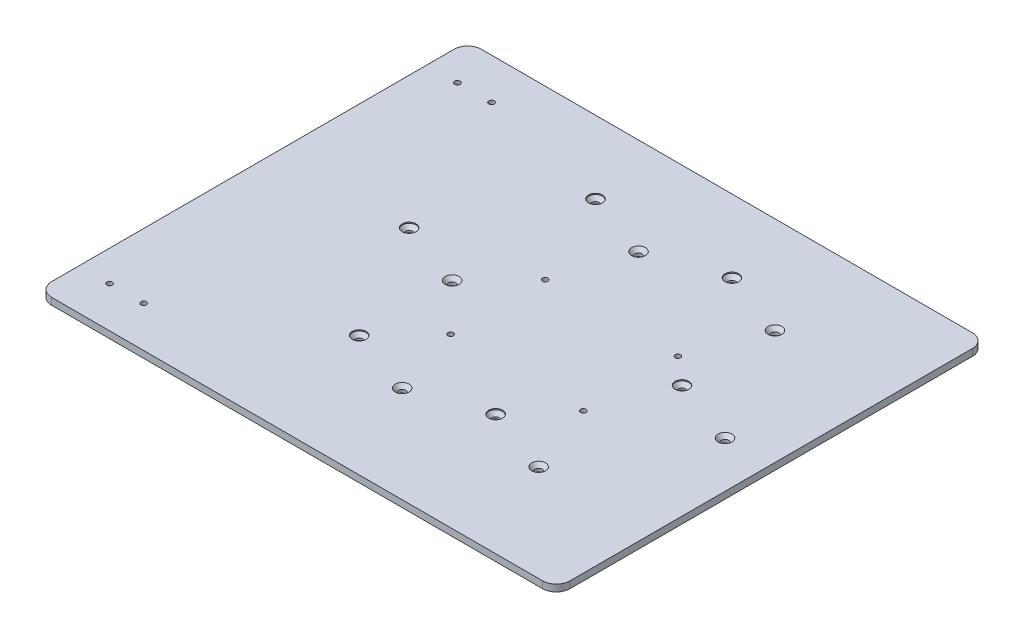
SolidWorks part; units mm, degrees
material "6061 Alloy"
ref_plane "Front Plane" through (0, 0, 0) normal (0, 0, 1) x (1, 0, 0)
ref_plane "Top Plane" through (0, 0, 0) normal (0, 1, 0) x (1, 0, 0)
ref_plane "Right Plane" through (0, 0, 0) normal (1, 0, 0) x (0, 0, -1)
sketch "Sketch1" plane through (0, 0, 0) normal (0, 1, 0) x (1, 0, 0)
  line L0 (0, 0) -> (0, 400)
  line L1 (0, 400) -> (500, 400)
  line L2 (500, 400) -> (500, 0)
  line L3 (500, 0) -> (0, 0)
  line L13 (0, 200) -> (500, 200) construction
  line L14 (250, 400) -> (250, 0) construction
  dimension "D1" = 500
  dimension "D2" = 400
extrude "Boss-Extrude1" add sketch "Sketch1" along normal blind 6.35
sketch "Sketch2" plane through (0, 6.35, 0) normal (0, 1, 0) x (1, 0, 0)
  line L0 (0, 200) -> (500, 200) construction
  line L1 (0, 400) -> (0, 0) construction
  line L2 (500, 0) -> (500, 400) construction
  line L3 (250, 400) -> (250, 0) construction
  line L4 (500, 400) -> (0, 400) construction
  line L5 (0, 0) -> (500, 0) construction
  line L15 (250, 200) -> (377, 200)
  line L16 (250, 200) -> (123, 200)
  line L17 (250, 200) -> (313.5, 309.9852)
  line L18 (250, 200) -> (186.5, 309.9852)
  line L19 (250, 200) -> (186.5, 90.0148)
  line L20 (250, 200) -> (313.5, 90.0148)
  circle A1 centre (250, 200) radius 127
  dimension "D1" = 60
  dimension "D2" = 60
  dimension "D3" = 60
  dimension "D4" = 60
  dimension "D5" = 60
  dimension "D6" = 60
hole_wizard "CSK for 1/4 Flat Head Machine Screw1" positions "3DSketch1" profile "Sketch3" countersink size "1/4" standard "Ansi Inch" end condition through all
sketch3d "3DSketch1"
  point P0 (313.5, 6.35, -309.9852)
  point P3 (186.5, 6.35, -309.9852)
  point P6 (123, 6.35, -200)
  point P9 (186.5, 6.35, -90.0148)
  point P12 (313.5, 6.35, -90.0148)
  point P15 (377, 6.35, -200)
sketch "Sketch3" plane through (313.5, 6.35, -309.9852) normal (1, 0, 0) x (0, 0, 1)
  line L0 (0, 0) -> (0, 6.35)
  line L1 (0, 6.35) -> (3.3782, 6.35)
  line L2 (3.3782, 6.35) -> (3.3782, 4.5209)
  line L3 (3.3782, 4.5209) -> (6.4389, 1)
  line L4 (6.4389, 1) -> (6.4389, 0)
  line L6 (6.4389, 0) -> (0, 0)
  line L7 (-3.3782, 4.5209) -> (-6.4389, 1) construction
  line L11 (0, -6.35) -> (0, 107.95) construction
  dimension "Thru Hole Dia." = 6.7564
  dimension "Thru Hole Depth" = 6.35
  dimension "C'Sink Dia." = 12.8778
  dimension "C'Sink Angle" = 82
  dimension "Head Clearance" = 1
sketch "Sketch4" plane through (0, 6.35, 0) normal (0, 1, 0) x (1, 0, 0)
  line L9 (377, 200) -> (250, 200)
  line L10 (250, 200) -> (312.5, 177.475)
  line L11 (312.5, 177.475) -> (377, 200)
  circle A1 centre (250, 200) radius 127
  point P10 (313.5, 309.9852)
  point P11 (186.5, 309.9852)
  point P13 (123, 200)
  dimension "D2" = 68.32
  dimension "D3" = 340.75
sketch "Sketch6" plane through (0, 0, 0) normal (0, 1, 0) x (1, 0, 0)
  line L0 (312.5, 177.475) -> (373.968, 177.475) construction
  line L1 (373.968, 177.475) -> (373.968, 400) construction
  line L2 (500, 400) -> (0, 400) construction
  line L3 (373.968, 177.475) -> (373.968, 0) construction
  line L5 (0, 0) -> (500, 0) construction
  line L6 (373.968, 360.2285) -> (351.616, 360.2285) construction
  line L7 (373.968, 301.5524) -> (225.632, 301.5524) construction
  line L8 (351.616, 133.475) -> (351.616, 221.475) construction
  line L9 (351.616, 221.475) -> (228.172, 221.475) construction
  line L10 (351.616, 133.475) -> (228.172, 133.475) construction
  point P18 (351.616, 177.475)
  dimension "D1" = 61.468
  dimension "D2" = 22.352
  dimension "D3" = 148.336
  dimension "D4" = 44
  dimension "D5" = 123.444
hole_wizard "CSK for #10 Flat Head Machine Screw1" positions "3DSketch3" profile "Sketch8" countersink size "#10" standard "Ansi Inch" end condition through all
sketch3d "3DSketch3"
  point P0 (351.616, 0, -133.475)
  point P3 (351.616, 0, -221.475)
  point P6 (228.172, 0, -221.475)
  point P9 (228.172, 0, -133.475)
sketch "Sketch8" plane through (351.616, 0, -133.475) normal (1, 0, 0) x (0, 0, -1)
  line L0 (0, 0) -> (0, 6.35)
  line L1 (0, 6.35) -> (2.5527, 6.35)
  line L2 (2.5527, 6.35) -> (2.5527, 2.6882)
  line L3 (2.5527, 2.6882) -> (4.8895, 0)
  line L5 (4.8895, 0) -> (0, 0)
  line L6 (-2.5527, 2.6882) -> (-4.8895, 0) construction
  line L11 (0, -6.35) -> (0, 107.95) construction
  dimension "Thru Hole Dia." = 5.1054
  dimension "Thru Hole Depth" = 6.35
  dimension "Near C'Sink Dia." = 9.779
  dimension "Near C'Sink Angle" = 82
sketch "Sketch12" plane through (0, 6.35, 0) normal (0, 1, 0) x (1, 0, 0)
  line L0 (500, 400) -> (500, 377.521)
  line L1 (500, 0) -> (500, 400) construction
  line L2 (500, 377.521) -> (0, 377.521)
  line L3 (0, 400) -> (0, 0) construction
  line L4 (0, 377.521) -> (0, 400)
  line L5 (0, 400) -> (500, 400)
  dimension "D1" = 22.479
extrude "Cut-Extrude2" cut sketch "Sketch12" against normal blind 6.35
sketch "Sketch13" plane through (0, 6.35, 0) normal (0, 1, 0) x (1, 0, 0)
  line L0 (0, 0) -> (0, -22.479)
  line L1 (0, 0) -> (500, 0)
  line L2 (500, 0) -> (500, -22.479)
  line L3 (500, -22.479) -> (0, -22.479)
  dimension "D1" = 22.479
extrude "Boss-Extrude2" add sketch "Sketch13" against normal blind 6.35
sketch "Sketch14" plane through (0, 0, 0) normal (0, -1, 0) x (1, 0, 0)
  line L3 (12.7, -15.621) -> (28.575, -15.621) construction
  line L4 (28.575, -15.621) -> (60.325, -15.621) construction
  line L5 (60.325, -15.621) -> (76.2, -15.621) construction
  line L6 (12.7, -339.421) -> (28.575, -339.421) construction
  line L7 (28.575, -339.421) -> (60.325, -339.421) construction
  line L8 (60.325, -339.421) -> (76.2, -339.421) construction
  line L13 (0, 22.479) -> (12.7, 22.479) construction
  line L14 (0, 22.479) -> (500, 22.479) construction
  line L15 (12.7, 22.479) -> (76.2, 22.479) construction
  line L16 (12.7, 22.479) -> (12.7, -15.621) construction
  line L18 (76.2, 22.479) -> (76.2, -15.621) construction
  line L19 (0, -177.521) -> (500, -177.521) construction
  line L20 (0, -377.521) -> (0, 22.479) construction
  line L21 (500, 22.479) -> (500, -377.521) construction
  line L22 (76.2, -377.521) -> (76.2, -339.421) construction
  line L24 (12.7, -377.521) -> (12.7, -339.421) construction
  line L25 (12.7, -377.521) -> (76.2, -377.521) construction
  line L26 (0, -377.521) -> (12.7, -377.521) construction
hole_wizard "CSK for #10 Flat Head Machine Screw2" positions "3DSketch7" profile "Sketch16" countersink size "#10" standard "Ansi Inch" end condition through all
sketch3d "3DSketch7"
  point P0 (60.325, 0, -15.621)
  point P3 (28.575, 0, -15.621)
  point P6 (60.325, 0, -339.421)
  point P9 (28.575, 0, -339.421)
sketch "Sketch16" plane through (60.325, 0, -15.621) normal (1, 0, 0) x (0, 0, -1)
  line L0 (0, 0) -> (0, 6.35)
  line L1 (0, 6.35) -> (2.5527, 6.35)
  line L2 (2.5527, 6.35) -> (2.5527, 2.6882)
  line L3 (2.5527, 2.6882) -> (4.8895, 0)
  line L5 (4.8895, 0) -> (0, 0)
  line L6 (-2.5527, 2.6882) -> (-4.8895, 0) construction
  line L11 (0, -6.35) -> (0, 107.95) construction
  dimension "Thru Hole Dia." = 5.1054
  dimension "Thru Hole Depth" = 6.35
  dimension "Near C'Sink Dia." = 9.779
  dimension "Near C'Sink Angle" = 82
sketch "Sketch20" plane through (0, 0, 0) normal (0, 1, 0) x (1, 0, 0)
  line L0 (186.5, 309.9852) -> (313.5, 90.0148) construction
  circle A0 centre (250, 200) radius 150
sketch "Sketch21" plane through (0, 6.35, 0) normal (0, 1, 0) x (1, 0, 0)
  line L7 (76.2, 342.5962) -> (12.7, 342.5962)
  line L16 (76.2, 336.2458) -> (12.7, 336.2458)
  line L18 (12.7, 342.5962) -> (12.7, 336.2458)
  line L19 (76.2, 342.5962) -> (76.2, 336.2458)
  line L22 (76.2, 12.4458) -> (76.2, 18.7962)
  line L23 (12.7, 12.4458) -> (12.7, 18.7962)
  line L24 (352.886, 109.125) -> (352.886, 245.825)
  line L25 (340.186, 109.125) -> (340.186, 245.825)
  line L26 (340.186, 245.825) -> (352.886, 245.825)
  line L27 (76.2, 18.7962) -> (12.7, 18.7962)
  line L28 (340.186, 109.125) -> (352.886, 109.125)
  line L29 (76.2, 12.4458) -> (12.7, 12.4458)
  line L30 (231.982, 109.125) -> (219.282, 109.125)
  line L31 (231.982, 245.825) -> (219.282, 245.825)
  line L32 (231.982, 109.125) -> (231.982, 245.825)
  line L33 (219.282, 109.125) -> (219.282, 245.825)
  point P28 (44.45, 336.2458)
  point P34 (44.45, 18.7962)
  point P41 (340.186, 177.475)
  point P44 (231.982, 177.475)
sketch "Sketch22" plane through (0, 6.35, 0) normal (0, 1, 0) x (1, 0, 0)
  line L0 (500, 377.521) -> (482.474, 377.521)
  line L1 (0, 377.521) -> (500, 377.521) construction
  line L2 (482.474, 377.521) -> (482.474, -22.479)
  line L3 (0, -22.479) -> (500, -22.479) construction
  line L4 (482.474, -22.479) -> (500, -22.479)
  line L5 (500, -22.479) -> (500, 377.521)
  dimension "D1" = 17.526
extrude "Cut-Extrude4" cut sketch "Sketch22" against normal blind 10
fillet "Fillet1" radius 12.7 4 edges at (482.474, 3.175, 22.479) (0, 3.175, 22.479) (0, 3.175, -377.521) (482.474, 3.175, -377.521)
sketch "Sketch25" plane through (0, 6.35, 0) normal (0, 1, 0) x (1, 0, 0)
  line L0 (351.616, 221.475) -> (312.5, 221.475) construction
  line L1 (312.5, 221.475) -> (312.5, 133.591) construction
  line L2 (351.616, 221.475) -> (312.5, 177.533) construction
  line L3 (312.5, 177.533) -> (369.5117, 177.533) construction
  line L4 (351.616, 133.591) -> (312.5, 177.533) construction
  line L5 (351.616, 133.591) -> (312.5, 133.591) construction
  line L9 (185.5, 177.533) -> (439.5, 177.533) construction
  line L10 (312.5, 177.533) -> (249, 287.5182) construction
  line L12 (312.5, 177.533) -> (376, 287.5182) construction
  line L13 (312.5, 177.533) -> (376, 67.5478) construction
  line L14 (312.5, 177.533) -> (249, 67.5478) construction
  circle A1 centre (312.5, 177.533) radius 127
  dimension "D1" = 39.116
  dimension "D2" = 43.942
  dimension "D3" = 60
  dimension "D5" = 60
  dimension "D8" = 60
  dimension "D9" = 60
hole_wizard "CSK for 1/4 Flat Head Machine Screw2" positions "3DSketch8" profile "Sketch28" countersink size "1/4" standard "Ansi Inch" end condition through all
sketch3d "3DSketch8"
  point P0 (249, 6.35, -287.5182)
  point P3 (376, 6.35, -287.5182)
  point P6 (439.5, 6.35, -177.533)
  point P9 (376, 6.35, -67.5478)
  point P12 (249, 6.35, -67.5478)
  point P15 (185.5, 6.35, -177.533)
sketch "Sketch28" plane through (249, 6.35, -287.5182) normal (1, 0, 0) x (0, 0, 1)
  line L0 (0, 0) -> (0, 6.35)
  line L1 (0, 6.35) -> (3.3782, 6.35)
  line L2 (3.3782, 6.35) -> (3.3782, 3.5209)
  line L3 (3.3782, 3.5209) -> (6.4389, 0)
  line L5 (6.4389, 0) -> (0, 0)
  line L6 (-3.3782, 3.5209) -> (-6.4389, 0) construction
  line L11 (0, -6.35) -> (0, 107.95) construction
  dimension "Thru Hole Dia." = 6.7564
  dimension "Thru Hole Depth" = 6.35
  dimension "Near C'Sink Dia." = 12.8778
  dimension "Near C'Sink Angle" = 82
